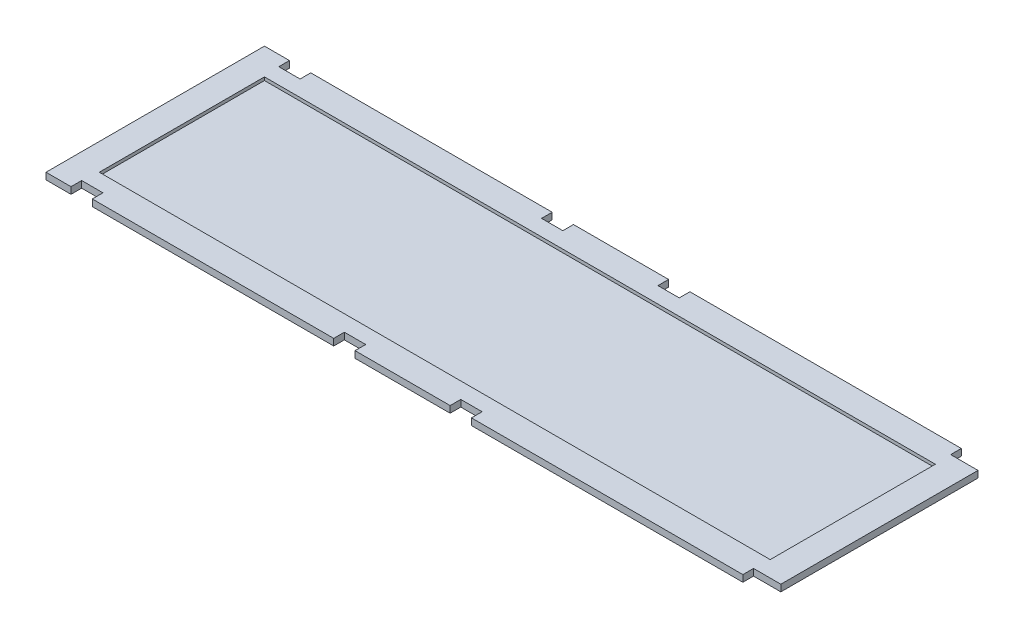
SolidWorks part; units mm, degrees
ref_plane "Front Plane" through (0, 0, 0) normal (0, 0, 1) x (1, 0, 0)
ref_plane "Top Plane" through (0, 0, 0) normal (0, 1, 0) x (1, 0, 0)
ref_plane "Right Plane" through (0, 0, 0) normal (1, 0, 0) x (0, 0, -1)
sketch "Sketch1" plane through (0, 0, 0) normal (0, 1, 0) x (1, 0, 0)
  line L0 (8.69, 0) -> (54, 0)
  line L1 (0, 0) -> (4.69, 0)
  line L2 (0, 0) -> (0, 41)
  line L3 (0, 41) -> (4.69, 41)
  line L4 (135.92, 2) -> (135.92, 39)
  line L6 (130.79, 41) -> (130.79, 39)
  line L7 (130.79, 39) -> (135.92, 39)
  line L10 (130.79, 0) -> (130.79, 2)
  line L11 (130.79, 2) -> (135.92, 2)
  line L14 (4.69, 41) -> (4.69, 39)
  line L15 (4.69, 39) -> (8.69, 39)
  line L16 (8.69, 41) -> (8.69, 39)
  line L18 (4.69, 0) -> (4.69, 2)
  line L19 (4.69, 2) -> (8.69, 2)
  line L20 (8.69, 0) -> (8.69, 2)
  line L21 (8.69, 41) -> (54, 41)
  line L22 (58, 41) -> (75.85, 41)
  line L24 (54, 41) -> (54, 39)
  line L25 (54, 39) -> (58, 39)
  line L26 (58, 41) -> (58, 39)
  line L28 (54, 0) -> (54, 2)
  line L29 (54, 2) -> (58, 2)
  line L30 (58, 0) -> (58, 2)
  line L31 (58, 0) -> (75.85, 0)
  line L32 (79.85, 41) -> (130.79, 41)
  line L34 (75.85, 41) -> (75.85, 39)
  line L35 (75.85, 39) -> (79.85, 39)
  line L36 (79.85, 41) -> (79.85, 39)
  line L38 (75.85, 0) -> (75.85, 2)
  line L39 (75.85, 2) -> (79.85, 2)
  line L40 (79.85, 0) -> (79.85, 2)
  line L41 (79.85, 0) -> (130.79, 0)
  dimension "D1" = 135.92
  dimension "D2" = 41
  dimension "D3" = 2
  dimension "D4" = 5.13
  dimension "D5" = 5.13
  dimension "D6" = 2
  dimension "D7" = 2
  dimension "D8" = 4
  dimension "D9" = 2
  dimension "D10" = 4
  dimension "D11" = 4.69
  dimension "D12" = 4.69
  dimension "D13" = 2
  dimension "D14" = 4
  dimension "D15" = 45.31
  dimension "D16" = 4
  dimension "D17" = 2
  dimension "D18" = 45.31
  dimension "D19" = 4
  dimension "D20" = 2
  dimension "D21" = 17.85
  dimension "D22" = 4
  dimension "D23" = 2
  dimension "D24" = 17.85
extrude "Boss-Extrude1" add sketch "Sketch1" along normal blind 1.25
sketch "Sketch2" plane through (0, 1.25, 0) normal (0, 1, 0) x (1, 0, 0)
  line L0 (0, 41) -> (0, 0) construction
  line L1 (5, 36) -> (130.92, 36)
  line L2 (5, 36) -> (5, 5)
  line L3 (5, 5) -> (130.92, 5)
  line L4 (130.92, 36) -> (130.92, 5)
  line L5 (54, 41) -> (8.69, 41) construction
  line L6 (8.69, 0) -> (54, 0) construction
  line L7 (135.92, 2) -> (135.92, 39) construction
  dimension "D1" = 5
  dimension "D2" = 5
  dimension "D3" = 5
  dimension "D4" = 5
extrude "Cut-Extrude1" cut sketch "Sketch2" against normal blind 0.6
